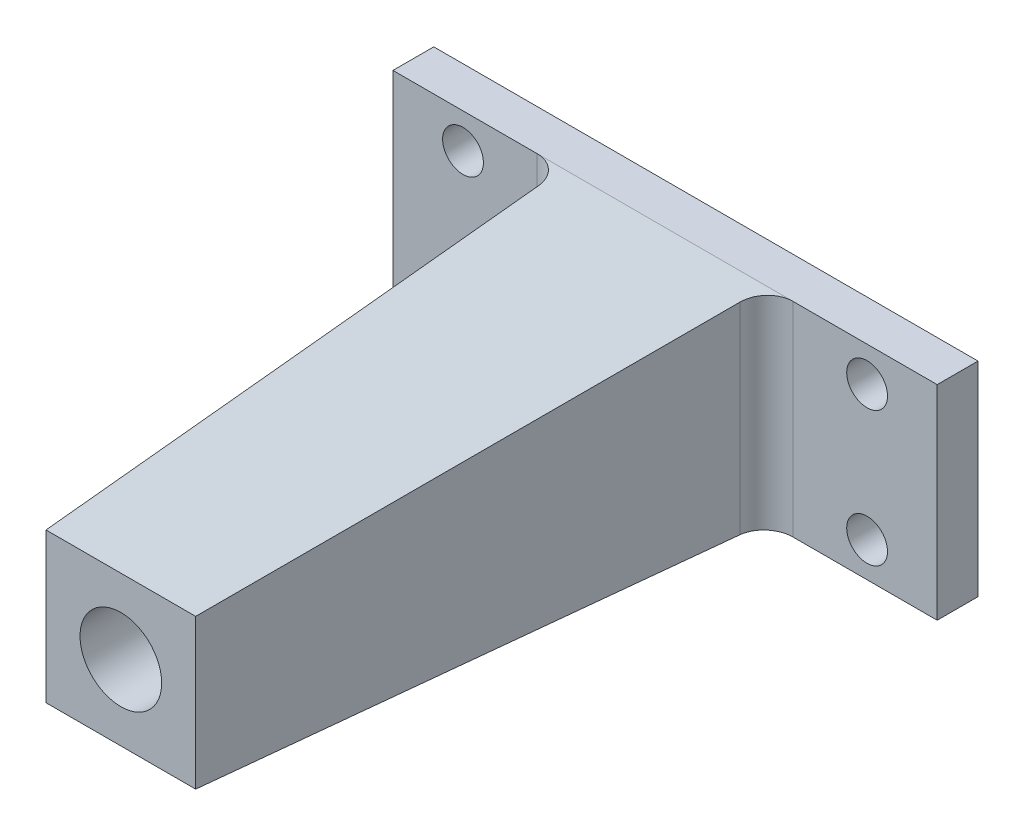
SolidWorks part; units mm, degrees
ref_plane "前视基准面" through (0, 0, 0) normal (0, 0, 1) x (1, 0, 0)
ref_plane "上视基准面" through (0, 0, 0) normal (0, 1, 0) x (1, 0, 0)
ref_plane "右视基准面" through (0, 0, 0) normal (1, 0, 0) x (0, 0, -1)
other "Configuration Table"
sketch "草图1" plane through (0, 0, 0) normal (0, 0, 1) x (1, 0, 0)
  line L1 (-20, -7.5) -> (20, -7.5)
  line L2 (-20, -7.5) -> (-20, 7.5)
  line L3 (-20, 7.5) -> (20, 7.5)
  line L4 (20, -7.5) -> (20, 7.5)
  line L5 (-20, -7.5) -> (20, 7.5) construction
  line L6 (-20, 7.5) -> (20, -7.5) construction
  line L7 (-4.95, -4.95) -> (4.95, -4.95) construction
  line L8 (-4.95, -4.95) -> (-4.95, 4.95) construction
  line L9 (-4.95, 4.95) -> (4.95, 4.95) construction
  line L10 (4.95, -4.95) -> (4.95, 4.95) construction
  line L11 (-4.95, -4.95) -> (4.95, 4.95) construction
  line L12 (-4.95, 4.95) -> (4.95, -4.95) construction
  circle A0 centre (0, 0) radius 3 construction
  circle A1 centre (4.95, 4.95) radius 1.5
  circle A2 centre (4.95, -4.95) radius 1.5
  circle A3 centre (-4.95, -4.95) radius 1.5
  circle A4 centre (-4.95, 4.95) radius 1.5
  dimension "D1" = 6
  dimension "D6" = 3
  dimension "D7" = 3
  dimension "D8" = 3
  dimension "D9" = 3
  dimension "D2" = 40
  dimension "D3" = 15
  dimension "D4" = 9.9
  dimension "D5" = 9.9
extrude "凸台-拉伸1" add sketch "草图1" along normal blind 3
sketch "草图2" plane through (0, 0, 3) normal (0, 0, 1) x (1, 0, 0)
  line L1 (-7.5, -7.5) -> (7.5, -7.5)
  line L2 (-7.5, -7.5) -> (-7.5, 7.5)
  line L3 (-7.5, 7.5) -> (7.5, 7.5)
  line L4 (7.5, -7.5) -> (7.5, 7.5)
  line L5 (-7.5, -7.5) -> (7.5, 7.5) construction
  line L6 (-7.5, 7.5) -> (7.5, -7.5) construction
  point P0 (0, 0)
  dimension "D1" = 15
  dimension "D2" = 15
ref_plane "基准面1" through (0, 0, 43) normal (0, 0, 1) x (1, 0, 0)
sketch "草图3" plane through (0, 0, 43) normal (0, 0, 1) x (1, 0, 0)
  line L8 (-5.5, -5.5) -> (5.5, -5.5)
  line L9 (5.5, -5.5) -> (5.5, 5.5)
  line L10 (5.5, 5.5) -> (-5.5, 5.5)
  line L11 (-5.5, 5.5) -> (-5.5, -5.5)
  line L12 (-5.5, -5.5) -> (5.5, -5.5)
  line L13 (5.5, -5.5) -> (5.5, 5.5)
  line L14 (5.5, 5.5) -> (-5.5, 5.5)
  line L15 (-5.5, 5.5) -> (-5.5, -5.5)
  dimension "D1" = 2
loft "放样1" add profiles "草图3", "草图2"
sketch "草图5" plane through (0, 0, 0) normal (0, 0, -1) x (-1, 0, 0)
  circle A0 centre (4.95, -4.95) radius 1.5 construction
  circle A1 centre (4.95, -4.95) radius 1.5
  circle A2 centre (4.95, 4.95) radius 1.5 construction
  circle A3 centre (-4.95, 4.95) radius 1.5 construction
  circle A4 centre (-4.95, -4.95) radius 1.5 construction
  circle A5 centre (4.95, 4.95) radius 1.5
  circle A6 centre (-4.95, 4.95) radius 1.5
  circle A7 centre (-4.95, -4.95) radius 1.5
extrude "切除-拉伸3" cut sketch "草图5" against normal blind 8
sketch "草图6" plane through (0, 0, 43) normal (0, 0, 1) x (1, 0, 0)
  line L8 (-7.5, 7.5) -> (-7.5, -7.5)
  line L9 (-7.5, -7.5) -> (7.5, -7.5)
  line L10 (7.5, -7.5) -> (7.5, 7.5)
  line L11 (7.5, 7.5) -> (-7.5, 7.5)
  line L12 (-7.5, 7.5) -> (-7.5, -7.5)
  line L13 (-7.5, -7.5) -> (7.5, -7.5)
  line L14 (7.5, -7.5) -> (7.5, 7.5)
  line L15 (7.5, 7.5) -> (-7.5, 7.5)
  dimension "D1" = 2
sketch "草图8" plane through (0, 0, 43) normal (0, 0, 1) x (1, 0, 0)
  circle A0 centre (0, 0) radius 2.9996
  dimension "D1" = 5.9993
extrude "切除-拉伸4" cut sketch "草图8" against normal blind 15
sketch "草图9" plane through (0, 0, 0) normal (0, 0, -1) x (-1, 0, 0)
  circle A0 centre (-14.849, -4.95) radius 1.5 construction
  circle A1 centre (-14.849, -4.95) radius 1.5
  circle A2 centre (-14.849, 4.9495) radius 1.5 construction
  circle A3 centre (-14.849, 4.9495) radius 1.5
  circle A4 centre (14.8495, 4.9495) radius 1.5 construction
  circle A5 centre (14.8495, 4.9495) radius 1.5
  circle A6 centre (14.8495, -4.95) radius 1.5 construction
  circle A7 centre (14.8495, -4.95) radius 1.5
extrude "切除-拉伸5" cut sketch "草图9" against normal blind 15
fillet "圆角1" radius 2 2 edges
